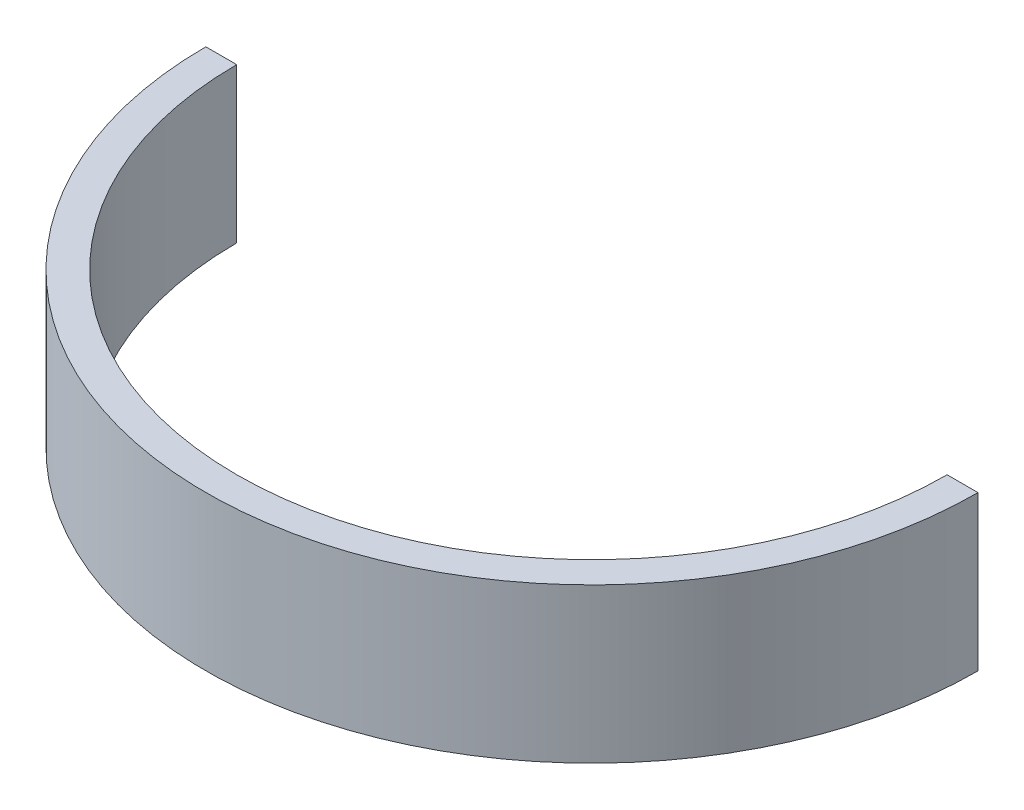
SolidWorks part; units mm, degrees
ref_plane "Front" through (0, 0, 0) normal (0, 0, 1) x (1, 0, 0)
ref_plane "Top" through (0, 0, 0) normal (0, 1, 0) x (1, 0, 0)
ref_plane "Right" through (0, 0, 0) normal (1, 0, 0) x (0, 0, -1)
sketch "草图1" plane through (0, 0, 0) normal (0, 1, 0) x (1, 0, 0)
  line L0 (-50, 0) -> (-46, 0)
  line L1 (46, 0) -> (50, 0)
  arc A0 (-50, 0) -> (50, 0) centre (0, 0) ccw
  arc A1 (-46, 0) -> (46, 0) centre (0, 0) ccw
extrude "凸台-拉伸1" add sketch "草图1" along normal blind 20
